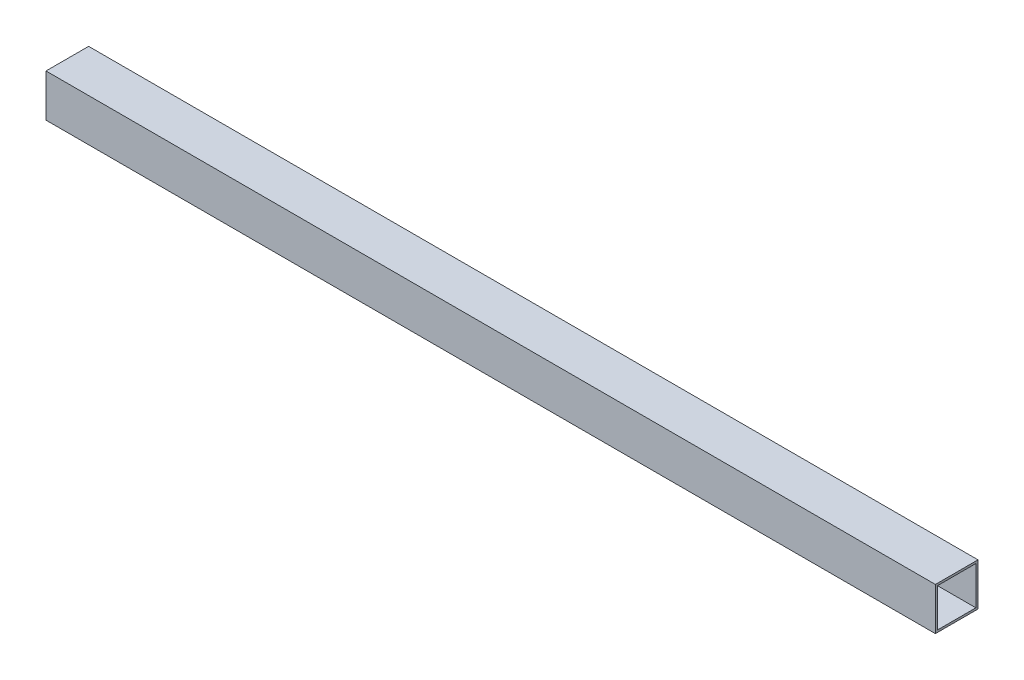
SolidWorks part; units mm, degrees
ref_plane "Front Plane" through (0, 0, 0) normal (0, 0, 1) x (1, 0, 0)
ref_plane "Top Plane" through (0, 0, 0) normal (0, 1, 0) x (1, 0, 0)
ref_plane "Right Plane" through (0, 0, 0) normal (1, 0, 0) x (0, 0, -1)
sketch "Sketch1" plane through (0, 0, 0) normal (0, 1, 0) x (1, 0, 0)
  line L1 (530, 25.4) -> (0, 25.4)
  line L2 (530, 25.4) -> (530, 0)
  line L3 (530, 0) -> (0, 0)
  line L4 (0, 25.4) -> (0, 0)
  point P4 (609.6, 293.0554)
  dimension "D1" = 530
  dimension "D2" = 25.4
extrude "Boss-Extrude1" add sketch "Sketch1" along normal blind 25.4
sketch "Sketch2" plane through (530, 0, 0) normal (1, 0, 0) x (0, 0, -1)
  line L1 (1.27, 24.13) -> (24.13, 24.13)
  line L2 (1.27, 24.13) -> (1.27, 1.27)
  line L3 (1.27, 1.27) -> (24.13, 1.27)
  line L4 (24.13, 24.13) -> (24.13, 1.27)
  line L5 (24.13, 24.13) -> (25.4, 24.13) construction
  line L6 (24.13, 24.13) -> (24.13, 25.4) construction
  line L7 (24.13, 25.4) -> (25.4, 25.4) construction
  line L8 (25.4, 24.13) -> (25.4, 25.4) construction
  line L9 (1.27, 1.27) -> (0, 1.27) construction
  line L10 (1.27, 1.27) -> (1.27, 0) construction
  line L11 (1.27, 0) -> (0, 0) construction
  line L12 (0, 1.27) -> (0, 0) construction
  dimension "D1" = 1.27
extrude "Cut-Extrude1" cut sketch "Sketch2" against normal through all
